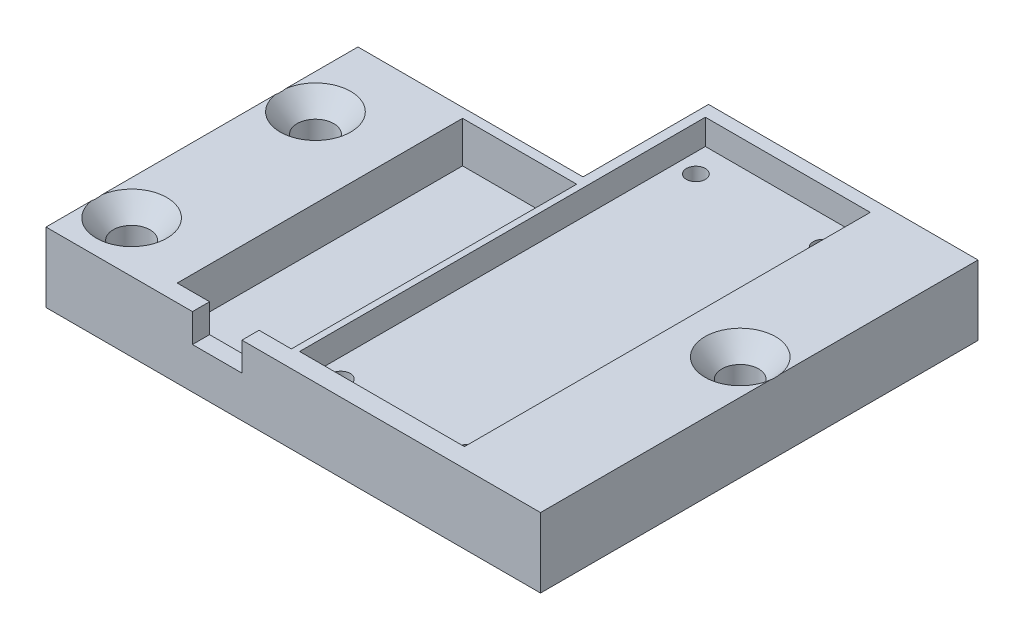
SolidWorks part; units mm, degrees
ref_plane "Front Plane" through (0, 0, 0) normal (0, 0, 1) x (1, 0, 0)
ref_plane "Top Plane" through (0, 0, 0) normal (0, 1, 0) x (1, 0, 0)
ref_plane "Right Plane" through (0, 0, 0) normal (1, 0, 0) x (0, 0, -1)
sketch "Sketch1" plane through (0, 0, 0) normal (0, 1, 0) x (1, 0, 0)
  line L1 (-54.9621, 22.0163) -> (23.0379, 22.0163)
  line L2 (-54.9621, 22.0163) -> (-54.9621, -46.9837)
  line L3 (-54.9621, -46.9837) -> (23.0379, -46.9837)
  line L4 (23.0379, 22.0163) -> (23.0379, -46.9837)
  dimension "D1" = 78
  dimension "D2" = 69
extrude "Boss-Extrude1" add sketch "Sketch1" along normal blind 11 contours L2 L3 L4 L1
sketch "Sketch4" plane through (0, 11, 0) normal (0, 1, 0) x (1, 0, 0)
  line L0 (-54.9621, 22.0163) -> (-54.9621, -46.9837) construction
  line L1 (-36.9621, -44.2837) -> (-18.9621, -44.2837)
  line L2 (-36.9621, -44.2837) -> (-36.9621, 0.7163)
  line L3 (-36.9621, 0.7163) -> (-18.9621, 0.7163)
  line L4 (-18.9621, -44.2837) -> (-18.9621, 0.7163)
  line L5 (-54.9621, -46.9837) -> (23.0379, -46.9837) construction
  dimension "D1" = 45
  dimension "D2" = 18
  dimension "D3" = 18
  dimension "D4" = 2.7
extrude "Cut-Extrude2" cut sketch "Sketch4" against normal blind 6.5
sketch "Sketch5" plane through (0, 11, 0) normal (0, 1, 0) x (1, 0, 0)
  line L0 (-36.9621, -44.2837) -> (-18.9621, -44.2837) construction
  line L1 (-24.0621, -44.2837) -> (-31.8621, -44.2837)
  line L2 (-24.0621, -44.2837) -> (-24.0621, -46.9837)
  line L3 (-24.0621, -46.9837) -> (-31.8621, -46.9837)
  line L4 (-31.8621, -44.2837) -> (-31.8621, -46.9837)
  line L5 (-54.9621, -46.9837) -> (23.0379, -46.9837) construction
  line L6 (23.0379, 22.0163) -> (23.0379, -46.9837) construction
  dimension "D1" = 23.1
  dimension "D2" = 47.1
extrude "Cut-Extrude3" cut sketch "Sketch5" against normal blind 4.5
sketch "Sketch6" plane through (0, 11, 0) normal (0, 1, 0) x (1, 0, 0)
  line L1 (-17.9621, -43.9837) -> (8.0379, -43.9837)
  line L2 (-17.9621, -43.9837) -> (-17.9621, 20.0163)
  line L3 (-17.9621, 20.0163) -> (8.0379, 20.0163)
  line L4 (8.0379, -43.9837) -> (8.0379, 20.0163)
  dimension "D2" = 64
  dimension "D4" = 26
extrude "Cut-Extrude4" cut sketch "Sketch6" against normal blind 4
sketch "Sketch8" plane through (0, 7, 0) normal (0, 1, 0) x (1, 0, 0)
  line L0 (23.0379, 22.0163) -> (23.0379, -46.9837) construction
  line L2 (-24.0621, -46.9837) -> (23.0379, -46.9837) construction
  line L3 (-54.9621, 22.0163) -> (-54.9621, -46.9837) construction
  line L4 (-54.9621, 22.0163) -> (23.0379, 22.0163) construction
  circle A0 centre (5.0379, -40.4837) radius 1.5
  circle A1 centre (-14.9621, -40.4837) radius 1.5
  circle A2 centre (-14.9621, 15.5163) radius 1.5
  circle A3 centre (5.0379, 15.5163) radius 1.5
  point P7 (23.0379, 22.0163)
  dimension "D1" = 3
  dimension "D4" = 3
  dimension "D5" = 3
  dimension "D6" = 3
  dimension "D2" = 18
  dimension "D3" = 6.5
  dimension "D7" = 6.5
  dimension "D8" = 40
  dimension "D9" = 18
  dimension "D10" = 40
  dimension "D11" = 6.5
  dimension "D12" = 6.5
extrude "Cut-Extrude5" cut sketch "Sketch8" against normal through all contours A3 | A2 | A0 | A1
sketch "Sketch9" plane through (0, 11, 0) normal (0, 1, 0) x (1, 0, 0)
  line L0 (-54.9621, -46.9837) -> (-31.8621, -46.9837) construction
  line L1 (-54.9621, 22.0163) -> (-54.9621, -46.9837) construction
  line L3 (-54.9621, 22.0163) -> (23.0379, 22.0163) construction
  line L4 (23.0379, 22.0163) -> (23.0379, -46.9837) construction
  circle A0 centre (-49.4621, -38.9837) radius 3.25
  circle A1 centre (-49.4621, -9.9837) radius 3.25
  circle A2 centre (17.5379, -9.9837) radius 3.25
  point P0 (-49.4621, -38.9837)
  point P5 (-49.4621, -9.9837)
  point P12 (17.5379, -9.9837)
  point P17 (0, 0)
  dimension "D5" = 6.5
  dimension "D6" = 6.5
  dimension "D9" = 6.5
  dimension "D1" = 8
  dimension "D2" = 5.5
  dimension "D3" = 5.5
  dimension "D4" = 32
  dimension "D7" = 5.5
  dimension "D8" = 32
hole_wizard "CSK for #12 Flat Head Machine Screw1" positions "Sketch21" profile "Sketch23" countersink size "#12" standard "ANSI Inch" end condition through all
sketch "Sketch21" plane through (0, 11, 0) normal (0, 1, 0) x (1, 0, 0)
  point P0 (-49.4621, -38.9837)
  point P3 (-49.4621, -9.9837)
  point P6 (17.5379, -9.9837)
sketch "Sketch23" plane through (-49.4621, 11, 38.9837) normal (1, 0, 0) x (0, 0, 1)
  line L0 (0, 0) -> (0, 11)
  line L1 (0, 11) -> (2.8956, 11)
  line L2 (2.8956, 11) -> (2.8956, 3.068)
  line L3 (2.8956, 3.068) -> (5.5626, 0)
  line L5 (5.5626, 0) -> (0, 0)
  line L6 (-2.8956, 3.068) -> (-5.5626, 0) construction
  line L11 (0, -6.35) -> (0, 107.95) construction
  dimension "Thru Hole Dia." = 5.7912
  dimension "Thru Hole Depth" = 11
  dimension "Near C'Sink Dia." = 11.1252
  dimension "Near C'Sink Angle" = 82
sketch "Sketch24" plane through (0, 11, 0) normal (0, 1, 0) x (1, 0, 0)
  line L0 (-54.9621, 22.0163) -> (-54.9621, -9.1515) construction
  line L1 (-54.9621, 2.2163) -> (-19.4621, 2.2163)
  line L2 (-54.9621, 2.2163) -> (-54.9621, 22.0163)
  line L3 (-54.9621, 22.0163) -> (-19.4621, 22.0163)
  line L4 (-19.4621, 2.2163) -> (-19.4621, 22.0163)
  line L5 (-54.9621, 22.0163) -> (23.0379, 22.0163) construction
  line L6 (-18.9621, 0.7163) -> (-36.9621, 0.7163) construction
  line L7 (-17.9621, 20.0163) -> (-17.9621, -43.9837) construction
  dimension "D1" = 1.5
  dimension "D2" = 1.5
extrude "Cut-Extrude7" cut sketch "Sketch24" against normal through all
